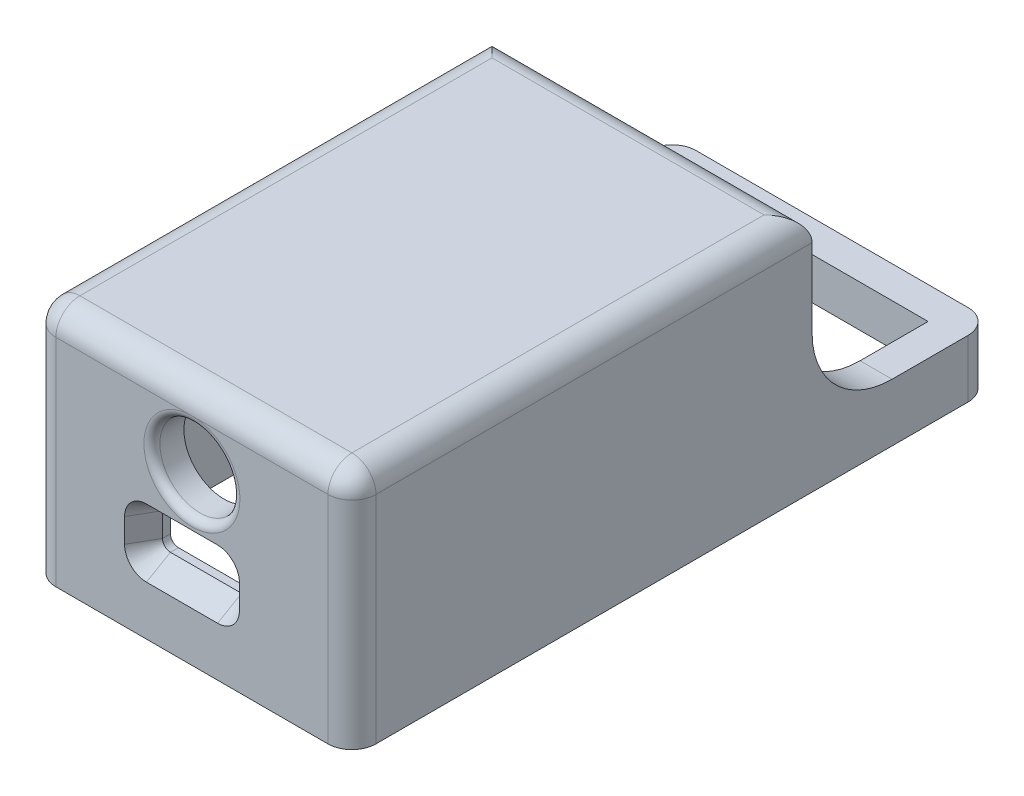
SolidWorks part; units mm, degrees
ref_plane "Front Plane" through (0, 0, 0) normal (0, 0, 1) x (1, 0, 0)
ref_plane "Top Plane" through (0, 0, 0) normal (0, 1, 0) x (1, 0, 0)
ref_plane "Right Plane" through (0, 0, 0) normal (1, 0, 0) x (0, 0, -1)
sketch "Sketch1" plane through (0, 0, 0) normal (0, 0, 1) x (1, 0, 0)
  line L1 (0, 0) -> (40, 0)
  line L2 (0, 0) -> (0, 30)
  line L3 (0, 30) -> (40, 30)
  line L4 (40, 0) -> (40, 30)
  dimension "D1" = 40
  dimension "D2" = 30
extrude "Boss-Extrude1" add sketch "Sketch1" along normal blind 80
shell "Shell1" thickness 4
sketch "Sketch2" plane through (0, 0, 76) normal (0, 0, -1) x (-1, 0, 0)
  line L0 (-15.7364, 9.136) -> (-11.4269, 9.136) construction
  line L1 (-14.3166, 9.9804) -> (-14.3166, 7.815) construction
  line L2 (-23.2066, 10.406) -> (-23.2066, 7.815) construction
  line L11 (-13.3166, 7.8977) -> (-24.2066, 7.8977)
  line L12 (-24.2066, 7.8977) -> (-24.2066, 12.8977)
  line L13 (-13.3166, 12.8977) -> (-24.2066, 12.8977)
  line L14 (-13.3166, 7.8977) -> (-13.3166, 12.8977)
extrude "Cut-Extrude1" cut sketch "Sketch2" against normal through all
fillet "Fillet1" radius 1 4 edges at (13.3166, 7.8977, 78) (13.3166, 12.8977, 78) (24.2066, 7.8977, 78) (24.2066, 12.8977, 78)
chamfer "Chamfer1" distance 3 angle 30 8 edges at (13.3166, 10.3977, 80) (18.7616, 7.8977, 80) (13.6095, 8.1906, 80) (23.9137, 8.1906, 80) (24.2066, 10.3977, 80) (13.6095, 12.6048, 80) (23.9137, 12.6048, 80) (18.7616, 12.8977, 80)
sketch "Sketch3" plane through (0, 0, 0) normal (-1, 0, 0) x (0, 0, 1)
  line L0 (80, 30) -> (0, 30) construction
  line L1 (0, 30) -> (22.5, 30)
  line L2 (0, 30) -> (0, 7.22)
  line L3 (0, 7.22) -> (22.5, 7.22)
  line L4 (22.5, 30) -> (22.5, 7.22)
  line L5 (80, 0) -> (0, 0) construction
  dimension "D1" = 7.22
  dimension "D2" = 22.5
extrude "Cut-Extrude2" cut sketch "Sketch3" against normal through all
sketch "Sketch4" plane through (0, 0, 80) normal (0, 0, 1) x (1, 0, 0)
  line L0 (40, 30) -> (0, 30) construction
  line L1 (40, 0) -> (40, 30) construction
  line L2 (40, 30) -> (0, 30) construction
  circle A0 centre (20, 21) radius 5
  point P8 (0, 0)
  point P9 (0, 0)
  point P10 (20, 30)
  dimension "D1" = 10
  dimension "D2" = 9
extrude "Cut-Extrude3" cut sketch "Sketch4" against normal blind 5
fillet "Fillet2" radius 1 1 edges at (25, 21, 80)
fillet "Fillet3" radius 10 2 edges at (2, 7.22, 22.5) (38, 7.22, 22.5)
fillet "Fillet4" radius 3 8 edges at (40, 15, 80) (0, 15, 80) (20, 30, 80) (40, 30, 51.25) (20, 30, 22.5) (0, 30, 51.25) (40, 3.61, 0) (0, 3.61, 0)
sketch "Sketch5" plane through (0, 0, 0) normal (0, -1, 0) x (1, 0, 0)
  line L34 (4, 76) -> (4, 4)
  line L35 (4, 4) -> (36, 4)
  line L36 (36, 4) -> (36, 76)
  line L37 (36, 76) -> (4, 76)
  line L38 (38.15, 78.15) -> (1.85, 78.15)
  line L39 (1.85, 1.85) -> (38.15, 1.85)
  line L40 (1.85, 78.15) -> (1.85, 1.85)
  line L41 (38.15, 1.85) -> (38.15, 78.15)
  line L42 (36.65, 78.15) -> (3.35, 78.15)
  line L43 (3.35, 1.85) -> (36.65, 1.85)
  line L44 (1.85, 76.65) -> (1.85, 3.35)
  line L45 (38.15, 3.35) -> (38.15, 76.65)
  line L46 (1.85, 78.15) -> (1.85, 1.85) construction
  line L47 (1.85, 1.85) -> (38.15, 1.85) construction
  line L48 (38.15, 1.85) -> (38.15, 78.15) construction
  line L49 (38.15, 78.15) -> (1.85, 78.15) construction
  arc A0 (1.85, 3.35) -> (3.35, 1.85) centre (3.35, 3.35) ccw
  arc A1 (38.15, 3.35) -> (36.65, 1.85) centre (36.65, 3.35) cw
  arc A2 (36.65, 78.15) -> (38.15, 76.65) centre (36.65, 76.65) cw
  arc A3 (1.85, 76.65) -> (3.35, 78.15) centre (3.35, 76.65) cw
  dimension "D3" = 1.5
  dimension "D1" = 2.15
  dimension "D2" = 2.15
extrude "Cut-Extrude4" cut sketch "Sketch5" against normal blind 2
